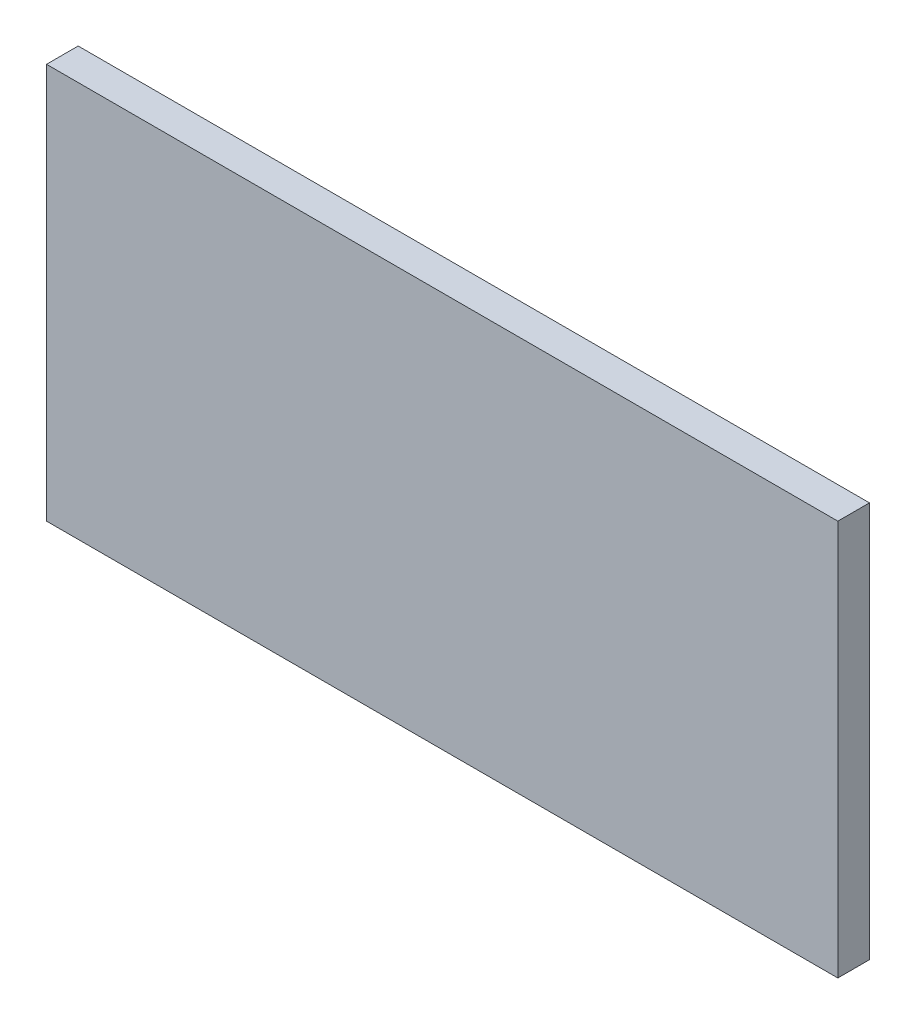
SolidWorks part; units mm, degrees
ref_plane "Plano frontal" through (0, 0, 0) normal (0, 0, 1) x (1, 0, 0)
ref_plane "Plano superior" through (0, 0, 0) normal (0, 1, 0) x (1, 0, 0)
ref_plane "Plano direito" through (0, 0, 0) normal (1, 0, 0) x (0, 0, -1)
sketch "Esboço1" plane through (0, 0, 0) normal (0, 0, 1) x (1, 0, 0)
  line L0 (125, 0) -> (-125, 0)
  line L1 (-125, 0) -> (-125, 125)
  line L2 (125, 0) -> (125, 125)
  line L3 (-125, 125) -> (125, 125)
  dimension "D1" = 250
extrude "Ressalto-extrusão1" add sketch "Esboço1" along normal blind 10
